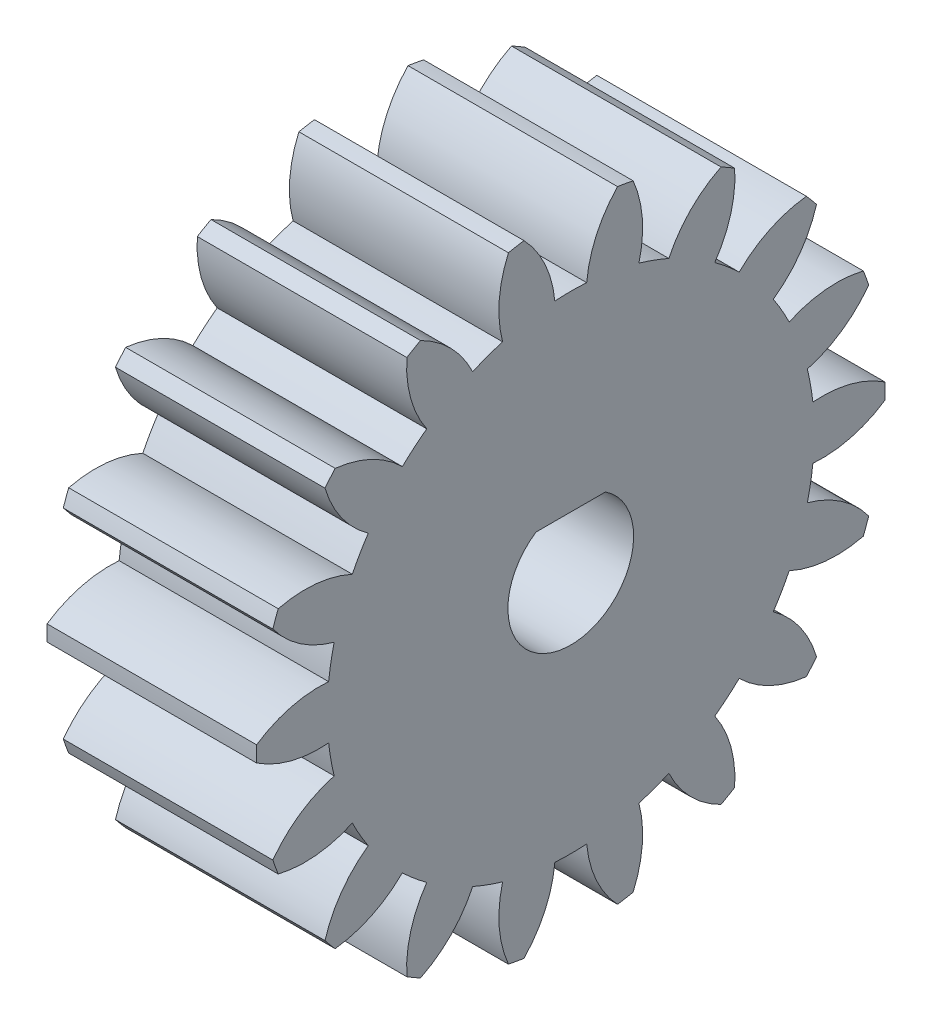
SolidWorks part; units mm, degrees
ref_plane "Plane1" through (0, 0, 0) normal (0, 0, 1) x (1, 0, 0)
ref_plane "Plane2" through (0, 0, 0) normal (0, 1, 0) x (1, 0, 0)
ref_plane "Plane3" through (0, 0, 0) normal (1, 0, 0) x (0, 0, -1)
sketch "HoldingSke" plane through (0, 0, 0) normal (0, 1, 0) x (1, 0, 0)
  line L0 (0, 0) -> (0.634, -0.206)
  line L1 (-15, 0) -> (100, 0) construction
  line L2 (0, 0) -> (-2.1039, 2.3779)
  line L3 (0, 0) -> (-11.863, 4.5341)
  line L4 (0, 0) -> (8.2133, 2.6687)
  line L5 (0, 0) -> (-46.8476, -17.4728)
  line L6 (0, 0) -> (-8.2896, -5.593)
  line L7 (-2.1039, 2.3779) -> (8.6586, 51.2059)
  line L8 (-76.2, 54.61) -> (-75.2, 54.61)
  line L9 (-71.009, 38.7566) -> (-53.1078, 45.2721)
  line L10 (-76.2, 71.12) -> (104.1128, 71.12)
  line L11 (0, 0) -> (-10, 0)
  line L12 (-76.2, 101.6) -> (-76.147, 101.6)
  line L13 (24.9733, 27.94) -> (52.9518, 28.4284)
  line L14 (24.9733, 27.94) -> (24.9743, 27.94)
  line L15 (24.9733, 27.94) -> (100.4006, 29.5858)
  line L16 (-63.627, -1.5) -> (-12.827, -1.5)
  circle A0 centre (0, 0) radius 3
  circle A1 centre (0, 0) radius 11.624
  circle A2 centre (0, 0) radius 37.5
  circle A3 centre (0, 0) radius 3
  dimension "MHD" = 23.248
  dimension "Hub_dia" = 75
  dimension "Bore" = 6
  dimension "MBD" = 6
  dimension "Num_teeth" = 18
  dimension "Pitch" = 0.6667
  dimension "Overall_len" = 50
  dimension "Show_teeth" = 18
  dimension "Thickness" = 10
  dimension "OAL" = 50.0001
  dimension "T_dim" = 1
  dimension "Ap" = 20
  dimension "H" = 19.05
  dimension "Pitch_radius" = 180.3128
  dimension "Width" = 10
  dimension "Backlash" = 0.053
  dimension "Addendum_fac" = 1
  dimension "Dedendum_fac" = 1.25
  dimension "Clearance_fac" = 0.25
  dimension "Dedendum_add" = 0.001
  dimension "Module" = 1.5
sketch "BasProSke" plane through (0, 0, 0) normal (0, 1, 0) x (1, 0, 0)
  line L0 (-10, 0) -> (60, 0) construction
  line L1 (0, 0) -> (0, 15)
  line L2 (0, 0) -> (10, 0)
  line L3 (10, 0) -> (10, 15)
  line L4 (10, 15) -> (0, 15)
  dimension "Thickness" = 10
  dimension "Diameter" = 30
revolve "Base-Revolve" add sketch "BasProSke" angle 360 about L0
sketch "TooCutSke" plane through (0, 0, 0) normal (1, 0, 0) x (0, 0, -1)
  line L1 (0, 0) -> (0, 107) construction
  line L2 (0, 0) -> (-1.2693, 13.4402) construction
  line L3 (0, 0) -> (-4.6734, 26.504) construction
  line L4 (-1.2693, 13.4402) -> (-2.3367, 13.252) construction
  arc A0 (0.76, 11.5991) -> (-0.76, 11.5991) centre (0, 0) ccw
  arc A1 (2.2542, 14.8553) -> (-2.2542, 14.8553) centre (0, 0) ccw
  circle A2 centre (0, 0) radius 13.5 construction
  circle A3 centre (0, 0) radius 12.6859 construction
  arc A4 (-0.76, 11.5991) -> (-2.2542, 14.8553) centre (-6.1371, 11.1026) ccw
  arc A5 (2.2542, 14.8553) -> (0.76, 11.5991) centre (6.1371, 11.1026) ccw
  dimension "Root_dia" = 23.248
  dimension "Overcut_dia" = 30.0508
  dimension "Pitch_dia" = 27
  dimension "Base_dia" = 25.3717
  dimension "Flank_rad" = 5.4
  dimension "Half_ang" = 10
  dimension "Half_CT" = 1.0839
extrude "ToothCut" cut sketch "TooCutSke" along normal through all
fillet "Breaks" [suppressed] radius 0.03
fillet "RootFillets" [suppressed] radius 0.376
pattern_circular "TeethCuts" count 18 every 20 about axis through (-10, 0, 0) along (1, 0, 0) of "ToothCut", "RootFillets", "Breaks"
sketch "HubNeaOneSke" plane through (0, 0, 0) normal (-1, 0, 0) x (0, 0, 1)
  circle A0 centre (0, 0) radius 11.624
  dimension "Diameter" = 23.248
extrude "HubNearOne" [suppressed] add sketch "HubNeaOneSke" along normal blind 40.0001
sketch "HubNeaBotSke" plane through (0, 0, 0) normal (-1, 0, 0) x (0, 0, 1)
  circle A0 centre (0, 0) radius 11.624
  dimension "Diameter" = 23.248
extrude "HubNearBoth" [suppressed] add sketch "HubNeaBotSke" along normal blind 20
ref_plane "FarPln" through (10, 0, 0) normal (1, 0, 0) x (0, 0, -1)
sketch "HubFarSke" plane through (10, 0, 0) normal (1, 0, 0) x (0, 0, -1)
  circle A0 centre (0, 0) radius 11.624
  dimension "Diameter" = 23.248
extrude "HubFar" [suppressed] add sketch "HubFarSke" along normal blind 20
sketch "BorSke" plane through (0, 0, 0) normal (1, 0, 0) x (0, 0, -1)
  circle A0 centre (0, 0) radius 3
  dimension "Diameter" = 6
extrude "Bore" cut sketch "BorSke" along normal mid plane 100.0001
sketch "KeySke" plane through (0, 0, 0) normal (1, 0, 0) x (0, 0, -1)
  line L0 (-1, 0) -> (-1, 4)
  line L1 (-1, 4) -> (1, 4)
  line L2 (1, 4) -> (1, 0)
  line L3 (0, 0) -> (0, 34) construction
  line L4 (-1, 0) -> (1, 0)
  dimension "Offset" = 4
  dimension "Width" = 2
extrude "Keyway" [suppressed] cut sketch "KeySke" along normal mid plane 100.0001
pattern_circular "Keyway2" [suppressed] count 2 every 90 about axis through (-10, 0, 0) along (1, 0, 0)
sketch "Sketch1" plane through (10, 0, 0) normal (1, 0, 0) x (0, 0, -1)
  line L0 (-1.6583, 2.5) -> (1.6583, 2.5)
  circle A0 centre (0, 0) radius 3
  dimension "D1" = 2.5
  dimension "D2" = 6
extrude "Boss-Extrude1" add sketch "Sketch1" against normal blind 10 contours L0 A0
equation "' \"Module@HoldingSke\" = 6.35"
equation "' \"Num_teeth@HoldingSke\" = 12"
equation "' \"Ap@HoldingSke\" =  20"
equation "' \"Ap@HoldingSke\" = 20"
equation "' \"Width@HoldingSke\" = 0.5 * 25.4"
equation "' \"Hub_dia@HoldingSke\"= 1 * 25.4"
equation "' \"Hub_dia@HoldingSke\" = 1 * 25.4"
equation "' \"Overall_len@HoldingSke\" = 1.0 * 25.4"
equation "' \"Bore@HoldingSke\" = 0.75 * 25.4"
equation "' \"T_dim@HoldingSke\" = 0.1 * 25.4"
equation "' \"Width@KeySke\" = 0.25 * 25.4"
equation "' \"Show_teeth@HoldingSke\" = 13"
equation "' \"Backlash@HoldingSke\" = 0.009 * 25.4"
equation "' \"Addendum_fac@HoldingSke\" = 1.0"
equation "' \"Dedendum_fac@HoldingSke\" = 1.25"
equation "' \"Dedendum_add@HoldingSke\" = 0.00005 * 25.4"
equation "' \"Clearance_fac@HoldingSke\" = 0.25"
equation "\"Pitch@HoldingSke\" = 1 / \"Module@HoldingSke\""
equation "\"Overcut_dia@TooCutSke\" = (\"Num_teeth@HoldingSke\" + 2 * \"Addendum_fac@HoldingSke\") / \"Pitch@HoldingSke\" + 0.002 * 25.4"
equation "\"Pitch_dia@TooCutSke\" = \"Num_teeth@HoldingSke\" / \"Pitch@HoldingSke\""
equation "\"Base_dia@TooCutSke\" = \"Num_teeth@HoldingSke\" / \"Pitch@HoldingSke\" * cos((\"Ap@HoldingSke\"  * 3.14159265 / 180))"
equation "\"Root_dia@TooCutSke\" = (\"Num_teeth@HoldingSke\" + 2) / \"Pitch@HoldingSke\" - 2 * (\"Addendum_fac@HoldingSke\" + \"Dedendum_fac@HoldingSke\") / \"Pitch@HoldingSke\" - \"Dedendum_add@HoldingSke\" * 2"
equation "\"Half_ang@TooCutSke\" = 180 / \"Num_teeth@HoldingSke\""
equation "\"Half_CT@TooCutSke\" = \"Num_teeth@HoldingSke\" / \"Pitch@HoldingSke\" * sin((3.14159265 / 2 / \"Num_teeth@HoldingSke\")) / 2 - 7 * \"Backlash@HoldingSke\" / 4"
equation "\"Flank_rad@TooCutSke\" = \"Num_teeth@HoldingSke\" / \"Pitch@HoldingSke\" / 5"
equation "\"Radius@RootFillets\" = \"Clearance_fac@HoldingSke\" / \"Pitch@HoldingSke\" + \"Dedendum_add@HoldingSke\""
equation "\"Break_rad@Breaks\" = 0.02 / \"Pitch@HoldingSke\""
equation "\"Thickness@HoldingSke\" = \"Width@HoldingSke\""
equation "\"OAL@HoldingSke\" = \"Thickness@HoldingSke\""
equation "\"MHD@HoldingSke\" = (\"Num_teeth@HoldingSke\" + 2) / \"Pitch@HoldingSke\" - 2 * (\"Addendum_fac@HoldingSke\" + \"Dedendum_fac@HoldingSke\")  / \"Pitch@HoldingSke\" - \"Dedendum_add@HoldingSke\" * 2"
equation "\"MBD@HoldingSke\" = (\"Num_teeth@HoldingSke\" + 2) / \"Pitch@HoldingSke\" - 2 * (\"Addendum_fac@HoldingSke\" + \"Dedendum_fac@HoldingSke\")  / \"Pitch@HoldingSke\" - \"Dedendum_add@HoldingSke\" * 2 - 0.002 * 25.4"
equation "\"MHD@HoldingSke\" = ((sgn( \"MHD@HoldingSke\" - \"Hub_dia@HoldingSke\" )-1)*( \"MHD@HoldingSke\" - \"Hub_dia@HoldingSke\" ))/-2+ \"Hub_dia@HoldingSke\""
equation "\"MBD@HoldingSke\" = ((sgn( \"MBD@HoldingSke\" - \"Bore@HoldingSke\" )-1)*( \"MBD@HoldingSke\" - \"Bore@HoldingSke\" ))/-2+ \"Bore@HoldingSke\""
equation "\"OAL@HoldingSke\" = ((sgn( \"OAL@HoldingSke\" - \"Overall_len@HoldingSke\" )+1)*( \"OAL@HoldingSke\" - \"Overall_len@HoldingSke\" ))/2 + \"Overall_len@HoldingSke\" + 0.000002 * 25.4"
equation "\"Num_teeth@TeethCuts\" = int( \"Show_teeth@HoldingSke\" ) + 1"
equation "\"Num_teeth@TeethCuts\" = ((sgn( \"Num_teeth@TeethCuts\" - \"Num_teeth@HoldingSke\" )-1)*( \"Num_teeth@TeethCuts\" - \"Num_teeth@HoldingSke\" ))/-2+ \"Num_teeth@HoldingSke\""
equation "\"Num_teeth@TeethCuts\" = ((sgn( \"Num_teeth@TeethCuts\" - 2.0)+1)*( \"Num_teeth@TeethCuts\" - 2.0))/2 +2.0"
equation "\"Angle@TeethCuts\" = 360.0 / \"Num_teeth@HoldingSke\""
equation "\"Diameter@BasProSke\" = (\"Num_teeth@HoldingSke\" + 2 * \"Addendum_fac@HoldingSke\") / \"Pitch@HoldingSke\""
equation "\"Thickness@BasProSke\"  = \"Thickness@HoldingSke\""
equation "' \"Fillet_rad@BasProSke\" =  \"Thickness@HoldingSke\" * 0.05"
equation "' \"Fillet_rad@BasProSke\" = \"Thickness@HoldingSke\" * 0.05"
equation "\"MHD@HoldingSke\" = ((sgn( \"MHD@HoldingSke\" - \"Root_dia@TooCutSke\" )-1)*( \"MHD@HoldingSke\" - \"Root_dia@TooCutSke\" ))/-2+ \"Root_dia@TooCutSke\""
equation "\"Diameter@HubNeaOneSke\" = \"MHD@HoldingSke\""
equation "\"Length@HubNearOne\" = \"OAL@HoldingSke\" - \"Thickness@BasProSke\""
equation "\"Diameter@HubNeaBotSke\" = \"MHD@HoldingSke\""
equation "\"Length@HubNearBoth\" = ( \"OAL@HoldingSke\" - \"Thickness@BasProSke\" ) / 2.0"
equation "\"Thickness@FarPln\" = \"Thickness@BasProSke\""
equation "\"Diameter@HubFarSke\" = \"MHD@HoldingSke\""
equation "\"Length@HubFar\" = ( \"OAL@HoldingSke\" - \"Thickness@BasProSke\" ) / 2.0"
equation "\"Diameter@BorSke\" = \"MBD@HoldingSke\""
equation "\"D1@Bore\" = \"OAL@HoldingSke\" * 2.0"
equation "\"D1@Keyway\" = \"OAL@HoldingSke\" * 2.0"
equation "\"Offset@KeySke\" = \"T_dim@HoldingSke\" + \"MBD@HoldingSke\" / 2.0"
